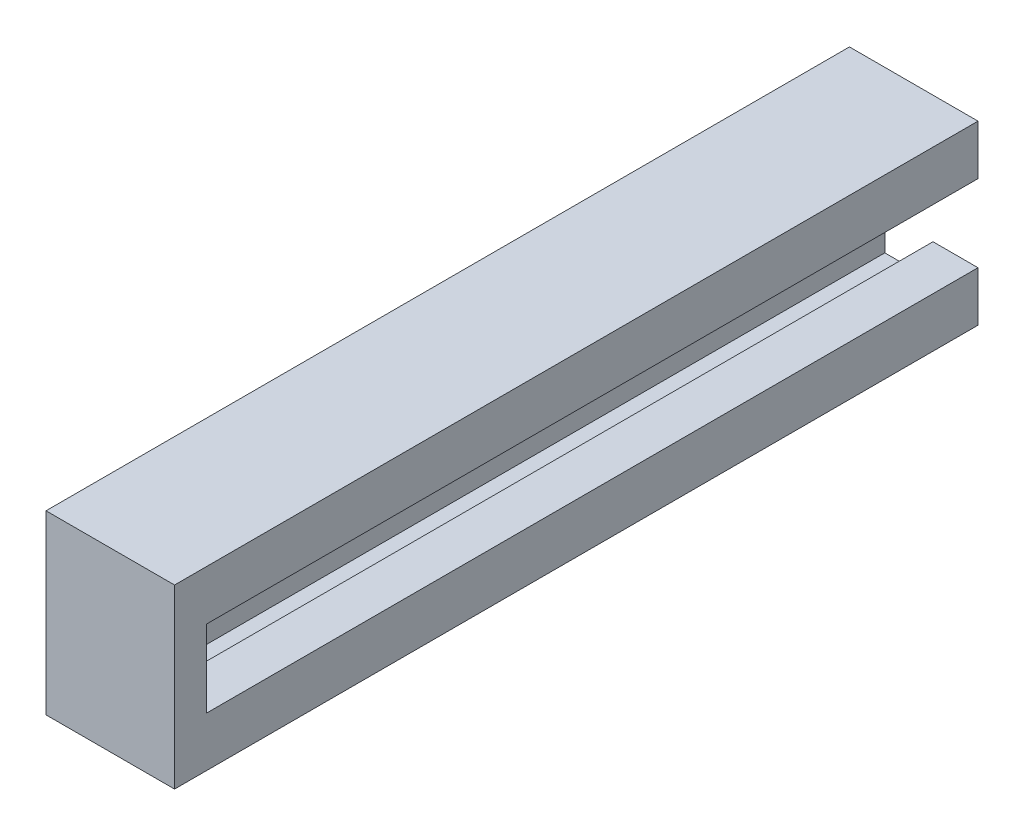
SolidWorks part; units mm, degrees
ref_plane "Front Plane" through (0, 0, 0) normal (0, 0, 1) x (1, 0, 0)
ref_plane "Top Plane" through (0, 0, 0) normal (0, 1, 0) x (1, 0, 0)
ref_plane "Right Plane" through (0, 0, 0) normal (1, 0, 0) x (0, 0, -1)
sketch "Sketch1" plane through (0, 0, 0) normal (0, 0, 1) x (1, 0, 0)
  line L0 (-11.5747, 6.3147) -> (8.4253, 6.3147)
  line L1 (8.4253, 6.3147) -> (8.4253, -1.4353)
  line L2 (8.4253, -1.4353) -> (1.9253, -1.4353)
  line L3 (1.9253, -1.4353) -> (1.9253, 3.8147)
  line L4 (1.9253, 3.8147) -> (-6.0747, 3.8147)
  line L5 (-6.0747, 3.8147) -> (-6.0747, -18.6853)
  line L6 (-6.0747, -18.6853) -> (1.4253, -18.6853)
  line L7 (1.4253, -18.6853) -> (1.4253, -13.4353)
  line L8 (1.4253, -13.4353) -> (8.4253, -13.4353)
  line L9 (8.4253, -13.4353) -> (8.4253, -21.1853)
  line L10 (8.4253, -21.1853) -> (-11.5747, -21.1853)
  line L11 (-11.5747, -21.1853) -> (-11.5747, 6.3147)
  dimension "D1" = 27.5
  dimension "D2" = 2.5
  dimension "D3" = 2.5
  dimension "D4" = 12
  dimension "D5" = 5.25
  dimension "D6" = 8
  dimension "D7" = 7.5
  dimension "D8" = 20
  dimension "D9" = 20
  dimension "D10" = 6.5
extrude "Boss-Extrude1" add sketch "Sketch1" along normal blind 120
sketch "Sketch2" plane through (0, 0, 120) normal (0, 0, 1) x (1, 0, 0)
  line L1 (8.4253, 6.3147) -> (-11.5747, 6.3147)
  line L2 (8.4253, 6.3147) -> (8.4253, -21.1853)
  line L3 (8.4253, -21.1853) -> (-11.5747, -21.1853)
  line L4 (-11.5747, 6.3147) -> (-11.5747, -21.1853)
extrude "Boss-Extrude2" add sketch "Sketch2" along normal blind 5
